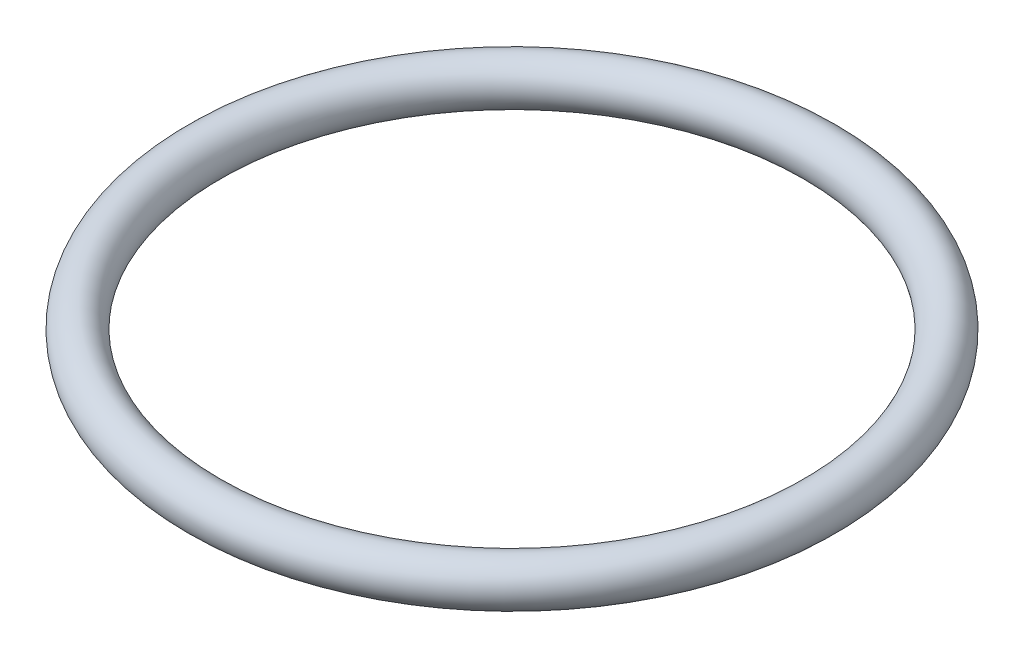
SolidWorks part; units mm, degrees
material "BUTYL"
ref_plane "Front Plane" through (0, 0, 0) normal (0, 0, 1) x (1, 0, 0)
ref_plane "Top Plane" through (0, 0, 0) normal (0, 1, 0) x (1, 0, 0)
ref_plane "Right Plane" through (0, 0, 0) normal (1, 0, 0) x (0, 0, -1)
sketch "Sketch2" plane through (0, 0, 0) normal (0, 0, 1) x (1, 0, 0)
  line L0 (0, 0) -> (10.8896, 0) construction
  line L1 (0, 0) -> (0, 2.4037) construction
  circle A0 centre (6.9, 0) radius 0.5
  point P3 (6.4, 0)
  dimension "D2" = 1
  dimension "D1" = 6.4
revolve "Revolve1" add sketch "Sketch2" angle 360 about L1
